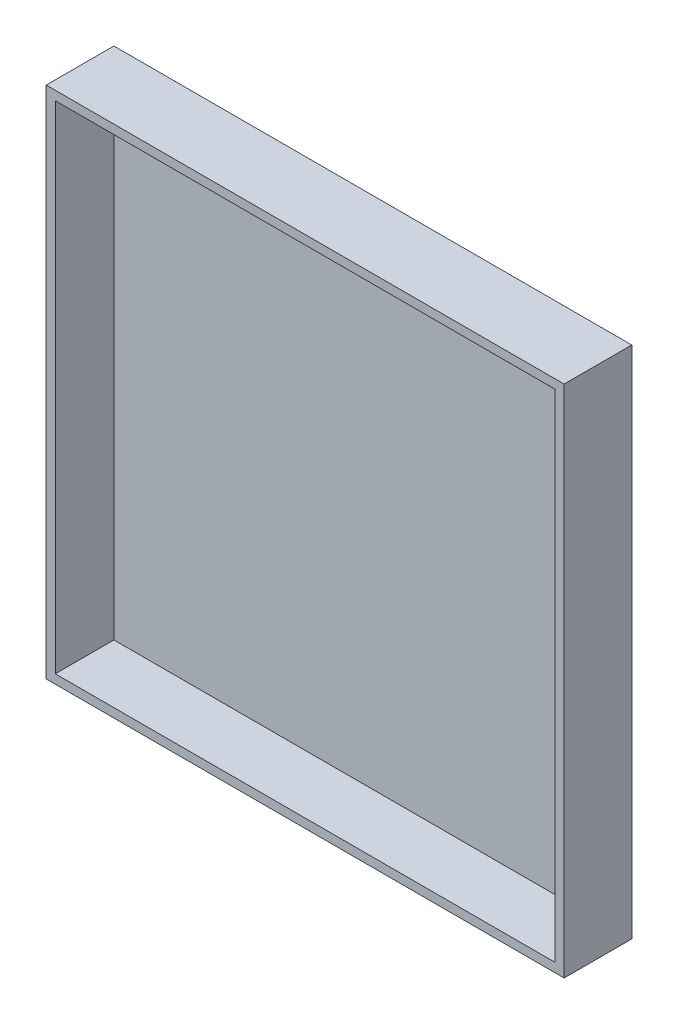
SolidWorks part; units mm, degrees
ref_plane "Přední rovina" through (0, 0, 0) normal (0, 0, 1) x (1, 0, 0)
ref_plane "Horní rovina" through (0, 0, 0) normal (0, 1, 0) x (1, 0, 0)
ref_plane "Pravá rovina" through (0, 0, 0) normal (1, 0, 0) x (0, 0, -1)
sketch "Skica1" plane through (0, 0, 0) normal (0, 0, 1) x (1, 0, 0)
  line L1 (4, 0) -> (-110.835, 0)
  line L2 (4, 0) -> (4, 114.06)
  line L3 (4, 114.06) -> (-110.835, 114.06)
  line L4 (-110.835, 0) -> (-110.835, 114.06)
  dimension "D1" = 114.835
  dimension "D2" = 114.06
extrude "Přidat vysunutím1" add sketch "Skica1" along normal blind 15 contours L3 L4 L1 L2
sketch "Skica2" plane through (0, 0, 15) normal (0, 0, 1) x (1, 0, 0)
  line L0 (-53.4175, 114.06) -> (-53.4175, 0) construction
  line L1 (4, 114.06) -> (-110.835, 114.06) construction
  line L2 (4, 0) -> (-110.835, 0) construction
  line L3 (4, 0) -> (4, 114.06) construction
  line L4 (-108.835, 2) -> (2, 2)
  line L5 (-108.835, 2) -> (-108.835, 112.06)
  line L6 (-108.835, 112.06) -> (2, 112.06)
  line L7 (2, 2) -> (2, 112.06)
  line L8 (-108.835, 2) -> (2, 112.06) construction
  line L9 (-108.835, 112.06) -> (2, 2) construction
  point P6 (-53.4175, 57.03)
  dimension "D1" = 2
  dimension "D2" = 2
extrude "Odebrat vysunutím1" cut sketch "Skica2" against normal blind 13
